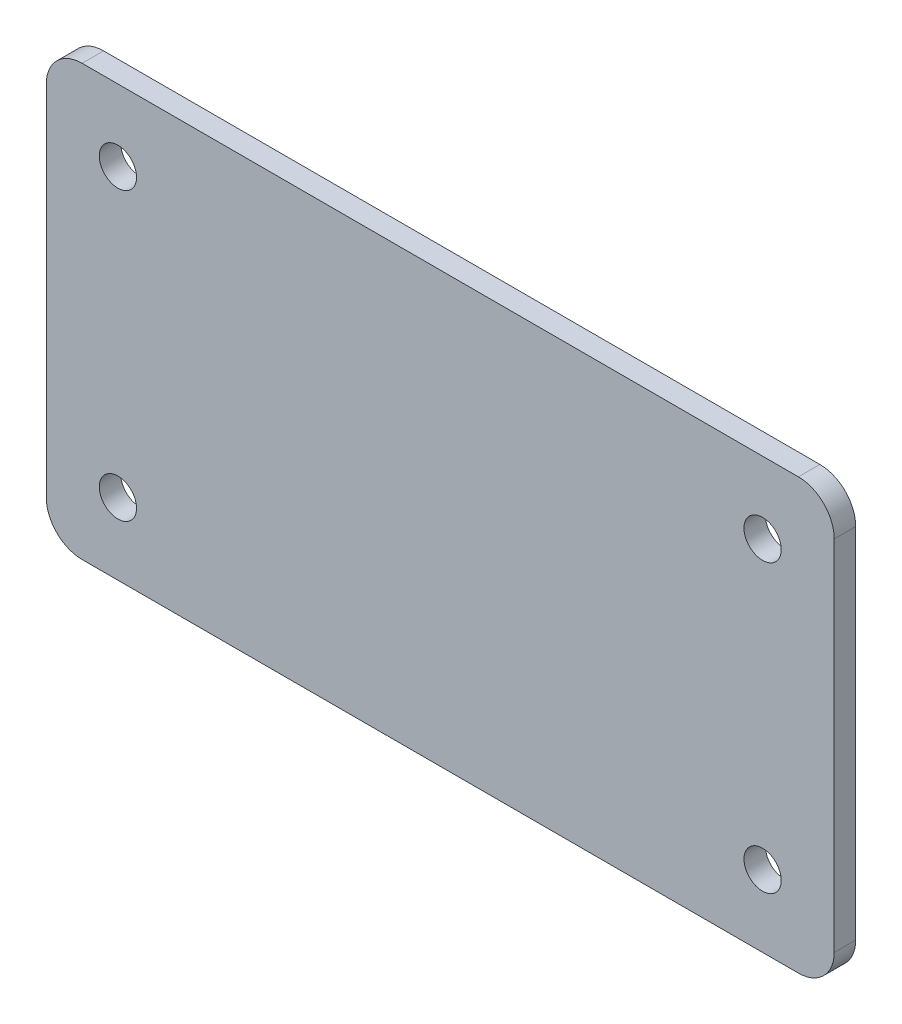
SolidWorks part; units mm, degrees
ref_plane "正面" through (0, 0, 0) normal (0, 0, 1) x (1, 0, 0)
ref_plane "平面" through (0, 0, 0) normal (0, 1, 0) x (1, 0, 0)
ref_plane "右側面" through (0, 0, 0) normal (1, 0, 0) x (0, 0, -1)
sketch "ｽｹｯﾁ2" plane through (0, 0, 0) normal (0, 0, 1) x (1, 0, 0)
  line L0 (0, -10) -> (110, -10) construction
  line L1 (0, 0) -> (110, 0)
  line L2 (0, 0) -> (0, -60)
  line L3 (0, -60) -> (110, -60)
  line L4 (110, 0) -> (110, -60)
  line L5 (0, -50) -> (110, -50) construction
  line L6 (10, -10) -> (10, -50) construction
  line L7 (100, -10) -> (100, -50) construction
  circle A0 centre (10, -10) radius 2.6
  circle A1 centre (100, -10) radius 2.6
  circle A2 centre (10, -50) radius 2.6
  circle A3 centre (100, -50) radius 2.6
  dimension "D4" = 5.2
  dimension "D5" = 10
  dimension "D6" = 10
  dimension "D7" = 40
  dimension "D1" = 10
  dimension "D2" = 110
  dimension "D8" = 10
extrude "ﾎﾞｽ - 押し出し1" add sketch "ｽｹｯﾁ2" along normal blind 3
fillet "ﾌｨﾚｯﾄ1" radius 5 4 edges at (0, -60, 1.5) (0, 0, 1.5) (110, -60, 1.5) (110, 0, 1.5)
